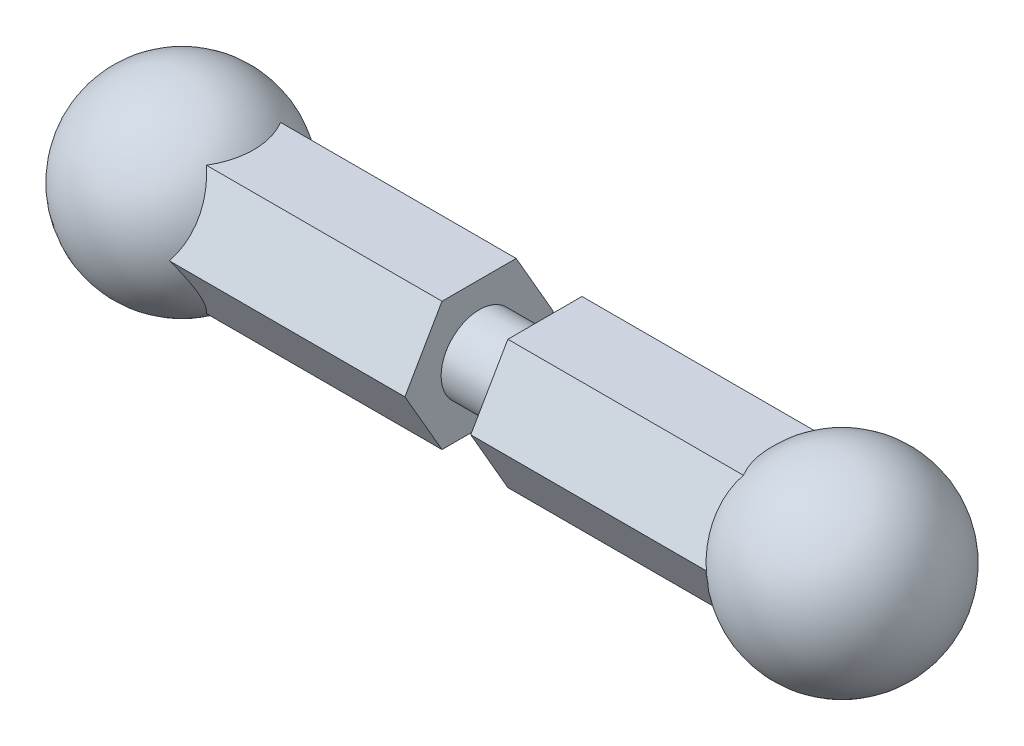
SolidWorks part; units mm, degrees
ref_plane "Front Plane" through (0, 0, 0) normal (0, 0, 1) x (1, 0, 0)
ref_plane "Top Plane" through (0, 0, 0) normal (0, 1, 0) x (1, 0, 0)
ref_plane "Right Plane" through (0, 0, 0) normal (1, 0, 0) x (0, 0, -1)
sketch "Sketch2" plane through (0, 0, 0) normal (0, 0, 1) x (1, 0, 0)
  line L5 (0, 3) -> (0, -3)
  arc A0 (0, 3) -> (0, -3) centre (0, 0) cw
  point P0 (0, -2.8473)
  dimension "D3" = 3
revolve "Revolve1" add sketch "Sketch2" angle 360 about L5
ref_point "Point1"
ref_plane "Plane3" through (20.55, 0, 0) normal (1, 0, 0) x (0, 0, -1)
sketch "Sketch7" plane through (20.55, 0, 0) normal (1, 0, 0) x (0, 0, -1)
  line L0 (0, 3) -> (0, -3)
  circle A0 centre (0, 0) radius 3 construction
  arc A1 (0, 3) -> (0, -3) centre (0, 0) cw
revolve "Revolve2" add sketch "Sketch7" angle 360 about L0
ref_point "Point2"
sketch "Sketch3" plane through (0, 0, 0) normal (1, 0, 0) x (0, 0, -1)
  line L1 (1.1547, -2) -> (2.3094, 0)
  line L2 (2.3094, 0) -> (1.1547, 2)
  line L3 (1.1547, 2) -> (-1.1547, 2)
  line L4 (-1.1547, 2) -> (-2.3094, 0)
  line L5 (-2.3094, 0) -> (-1.1547, -2)
  line L6 (-1.1547, -2) -> (1.1547, -2)
  circle A0 centre (0, 0) radius 2 construction
  point P1 (0, 0)
  point P9 (0, 0)
  dimension "D1" = 4
extrude "Boss-Extrude2" add sketch "Sketch3" along normal blind 9.25 contours L4 L5 L6 L1 L2 L3
ref_plane "Plane4" through (10.275, 0, 0) normal (1, 0, 0) x (0, 0, -1)
mirror "Mirror3" about plane through (10.275, 0, 0) normal (1, 0, 0) of "Boss-Extrude2"
sketch "Sketch5" plane through (9.25, 0, 0) normal (1, 0, 0) x (0, 0, -1)
  line L0 (-2.3094, 0) -> (-1.1827, 0) construction
  circle A0 centre (0.0079, 0) radius 1.1906
  dimension "D1" = 2.3813
extrude "Boss-Extrude3" add sketch "Sketch5" along normal up to surface (2.05 mm away) up to face at (11.3, 0, 0)
